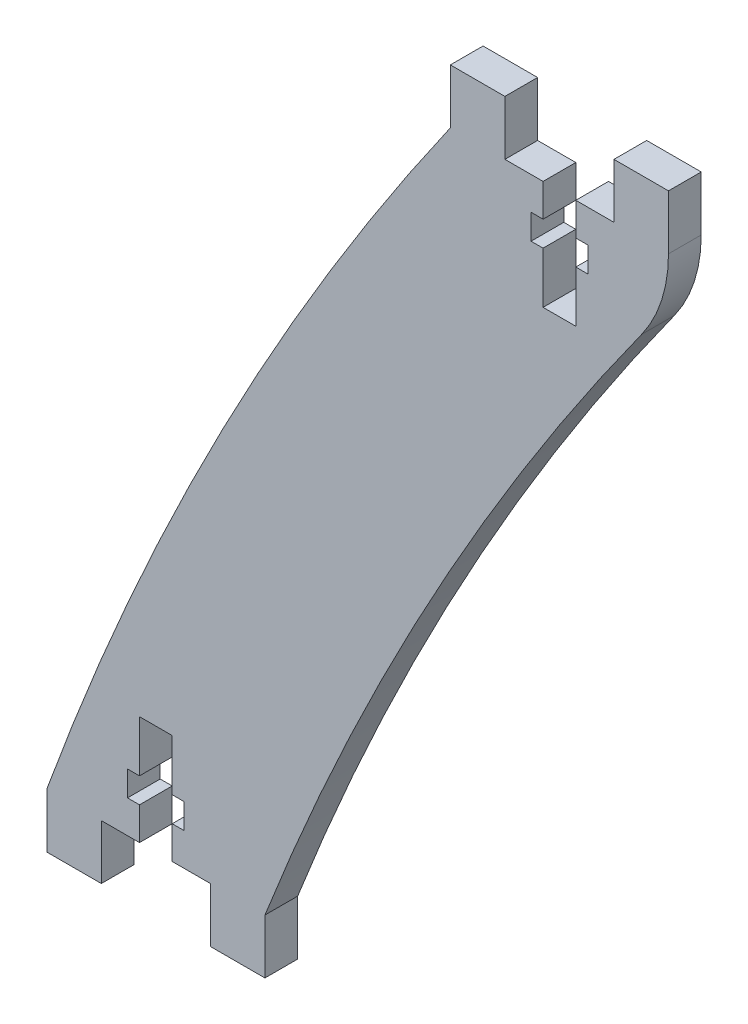
SolidWorks part; units mm, degrees
ref_plane "Front Plane" through (0, 0, 0) normal (0, 0, 1) x (1, 0, 0)
ref_plane "Top Plane" through (0, 0, 0) normal (0, 1, 0) x (1, 0, 0)
ref_plane "Right Plane" through (0, 0, 0) normal (1, 0, 0) x (0, 0, -1)
sketch "Sketch1" plane through (0, 0, 0) normal (0, 0, 1) x (1, 0, 0)
  line L0 (13, 0) -> (13, 71) construction
  line L1 (23, 0) -> (23, 65.2704) construction
  line L2 (13, 71) -> (70, 71) construction
  line L3 (13, 0) -> (21.9506, 24.5916) construction
  line L4 (0, 0) -> (61.5031, 0) construction
  line L5 (70, 71) -> (70, 49.2739) construction
  line L6 (60, 71) -> (60, 55.7792) construction
  line L7 (61.5, 71) -> (65, 71)
  line L8 (65, 76) -> (70, 76)
  line L9 (70, 76) -> (70, 71)
  line L10 (65, 76) -> (65, 71)
  line L11 (58.5, 71) -> (55, 71)
  line L12 (55, 71) -> (55, 76)
  line L13 (55, 76) -> (50, 76)
  line L14 (50, 76) -> (50, 71)
  line L15 (61.5, 71) -> (58.5, 71) construction
  line L16 (58.5, 71) -> (58.5, 68)
  line L17 (58.5, 65.7) -> (57.4, 65.7)
  line L18 (62.6, 68) -> (62.6, 65.7)
  line L19 (57.4, 68) -> (58.5, 68)
  line L20 (58.5, 65.7) -> (58.5, 61)
  line L21 (58.5, 61) -> (61.5, 61)
  line L22 (61.5, 61) -> (61.5, 65.7)
  line L23 (61.5, 68) -> (62.6, 68)
  line L24 (57.4, 65.7) -> (57.4, 68)
  line L25 (62.6, 65.7) -> (61.5, 65.7)
  line L26 (61.5, 68) -> (61.5, 71)
  line L27 (60, 61) -> (60, 71) construction
  line L28 (23, 0) -> (23, 11.2208) construction
  line L29 (21.5, 0) -> (18, 0)
  line L30 (18, -5) -> (13, -5)
  line L31 (13, -5) -> (13, 0)
  line L32 (18, -5) -> (18, 0)
  line L33 (24.5, 0) -> (28, 0)
  line L34 (28, 0) -> (28, -5)
  line L35 (28, -5) -> (33, -5)
  line L36 (33, -5) -> (33, 0)
  line L37 (21.5, 0) -> (24.5, 0) construction
  line L38 (24.5, 0) -> (24.5, 3)
  line L39 (24.5, 5.3) -> (25.6, 5.3)
  line L40 (20.4, 3) -> (20.4, 5.3)
  line L41 (25.6, 3) -> (24.5, 3)
  line L42 (24.5, 5.3) -> (24.5, 10)
  line L43 (24.5, 10) -> (21.5, 10)
  line L44 (21.5, 10) -> (21.5, 5.3)
  line L45 (21.5, 3) -> (20.4, 3)
  line L46 (25.6, 5.3) -> (25.6, 3)
  line L47 (20.4, 5.3) -> (21.5, 5.3)
  line L48 (21.5, 3) -> (21.5, 0)
  line L49 (23, 10) -> (23, 0) construction
  arc A0 (13, 0) -> (50, 71) centre (300.2349, -104.545) cw
  arc A1 (70, 71) -> (67.5334, 63.3661) centre (56.9539, 71) cw
  arc A2 (67.5334, 63.3661) -> (33, 0) centre (300.2349, -104.545) ccw
  dimension "D1" = 71
  dimension "D2" = 23
  dimension "D3" = 5.2
  dimension "D4" = 20
  dimension "D5" = 10
  dimension "D6" = 5
  dimension "D7" = 5
  dimension "D8" = 3
  dimension "D9" = 2.3
  dimension "D10" = 3
  dimension "D11" = 10
  dimension "D12" = 10
  dimension "D13" = 5
  dimension "D14" = 5
  dimension "D15" = 5.2
  dimension "D16" = 3
  dimension "D17" = 2.3
  dimension "D18" = 3
  dimension "D19" = 10
  dimension "D20" = 60
extrude "Boss-Extrude1" add sketch "Sketch1" along normal blind 3
